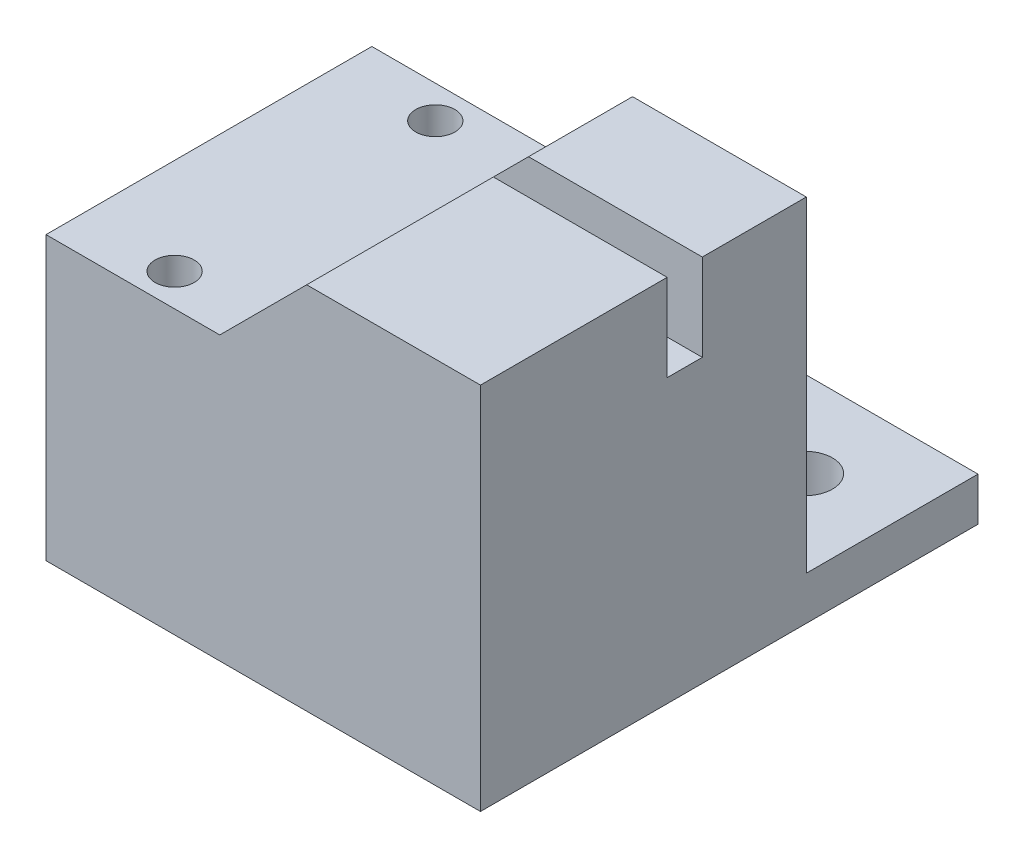
SolidWorks part; units mm, degrees
ref_plane "前视基准面" through (0, 0, 0) normal (0, 0, 1) x (1, 0, 0)
ref_plane "上视基准面" through (0, 0, 0) normal (0, 1, 0) x (1, 0, 0)
ref_plane "右视基准面" through (0, 0, 0) normal (1, 0, 0) x (0, 0, -1)
sketch "草图1" plane through (0, 0, 0) normal (0, 1, 0) x (1, 0, 0)
  line L1 (-100, 75) -> (100, 75)
  line L2 (-100, 75) -> (-100, -75)
  line L3 (-100, -75) -> (100, -75)
  line L4 (100, 75) -> (100, -75)
  line L5 (-100, 75) -> (100, -75) construction
  line L6 (-100, -75) -> (100, 75) construction
  point P0 (0, 0)
  dimension "D1" = 200
  dimension "D2" = 150
extrude "凸台-拉伸1" add sketch "草图1" along normal blind 180
sketch "草图2" plane through (0, 0, 0) normal (0, 0, 1) x (1, 0, 0)
  line L0 (-100, 180) -> (30, 180)
  line L1 (-100, 180) -> (100, 180) construction
  line L3 (30, 180) -> (-20, 130)
  line L4 (-20, 130) -> (-100, 130)
  line L5 (-100, 180) -> (-100, 0) construction
  line L6 (-100, 130) -> (-100, 180)
  dimension "D1" = 45
  dimension "D2" = 50
  dimension "D3" = 130
extrude "切除-拉伸1" cut sketch "草图2" against normal mid plane 200
sketch "草图3" plane through (0, 180, 0) normal (0, 1, 0) x (1, 0, 0)
  line L0 (100, -75) -> (100, 75) construction
  line L1 (100, 27.1277) -> (-20, 27.1277)
  line L2 (100, 27.1277) -> (100, 10.9456)
  line L3 (100, 10.9456) -> (-20, 10.9456)
  line L4 (-20, 27.1277) -> (-20, 10.9456)
  line L5 (-20, 75) -> (-20, -75) construction
extrude "切除-拉伸2" cut sketch "草图3" against normal up to surface (50 mm away) up to face at (-60, 130, 0)
sketch "草图4" plane through (0, 130, 0) normal (0, 1, 0) x (1, 0, 0)
  line L0 (0, 0) -> (-73.4518, 0) construction
  circle A0 centre (-55.7869, 60) radius 9
  circle A1 centre (-55.7869, -60) radius 9
  dimension "D1" = 120
  dimension "D2" = 18
extrude "切除-拉伸3" cut sketch "草图4" against normal blind 20
ref_plane "基准面1" through (0, 0, -19.0366) normal (0, 0, 1) x (1, 0, 0)
sketch "草图5" plane through (100, 0, 0) normal (1, 0, 0) x (0, 0, -1)
  line L0 (154.0366, -20) -> (154.0366, 0) construction
  line L1 (75, 0) -> (154.0366, 0)
  line L2 (75, 0) -> (75, 20)
  line L3 (75, 20) -> (154.0366, 20)
  line L4 (154.0366, 0) -> (154.0366, 20)
  dimension "D1" = 20
extrude "凸台-拉伸2" add sketch "草图5" against normal up to surface (200 mm away) up to face at (-100, 65, 0)
sketch "草图6" plane through (0, 20, 0) normal (0, 1, 0) x (1, 0, 0)
  line L0 (-100, 114.5183) -> (100, 114.5183) construction
  line L1 (-100, 75) -> (-100, 154.0366) construction
  line L2 (100, 154.0366) -> (100, 75) construction
  circle A0 centre (-60, 114.5183) radius 12.5
  circle A1 centre (60, 114.5183) radius 12.5
  dimension "D1" = 25
  dimension "D2" = 40
  dimension "D3" = 40
extrude "切除-拉伸4" cut sketch "草图6" against normal blind 210
ref_plane "基准面2" through (0, 0, -19.0366) normal (0, 0, 1) x (1, 0, 0)
sketch "草图7" plane through (0, 0, 75) normal (0, 0, 1) x (1, 0, 0)
  line L0 (20, 170) -> (112.3889, 170)
  line L1 (30, 180) -> (-20, 130) construction
  line L2 (112.3889, 170) -> (112.3889, 195.8217)
  line L3 (112.3889, 195.8217) -> (6.5138, 195.8217)
  line L4 (6.5138, 195.8217) -> (20, 170)
  line L5 (30, 180) -> (100, 180) construction
  dimension "D1" = 10
extrude "切除-拉伸5" cut sketch "草图7" against normal through all both and the other way through all
